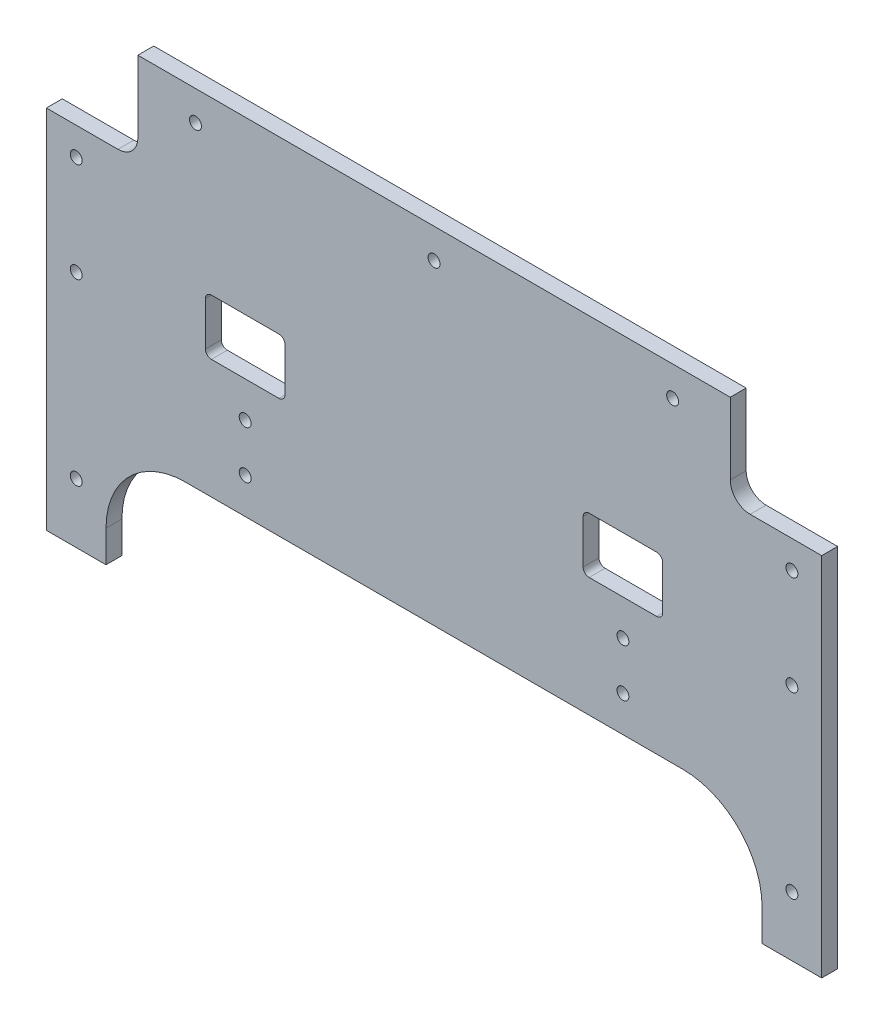
SolidWorks part; units mm, degrees
material "Thornel Mat VMA"
ref_plane "前视基准面" through (0, 0, 0) normal (0, 0, 1) x (1, 0, 0)
ref_plane "上视基准面" through (0, 0, 0) normal (0, 1, 0) x (1, 0, 0)
ref_plane "右视基准面" through (0, 0, 0) normal (1, 0, 0) x (0, 0, -1)
sketch "草图1" plane through (0, 0, 0) normal (0, 0, 1) x (1, 0, 0)
  line L1 (-97.5, 25) -> (97.5, 25)
  line L2 (-97.5, 25) -> (-97.5, -25)
  line L3 (-97.5, -25) -> (97.5, -25)
  line L4 (97.5, 25) -> (97.5, -25)
  line L5 (-97.5, 25) -> (97.5, -25) construction
  line L6 (-97.5, -25) -> (97.5, 25) construction
  point P0 (0, 0)
  dimension "D1" = 195
  dimension "D2" = 50
extrude "凸台-拉伸1" add sketch "草图1" along normal blind 4
sketch "草图5" plane through (0, 0, 4) normal (0, 0, 1) x (1, 0, 0)
  line L0 (0, 0) -> (0, 50) construction
  line L1 (97.5, 25) -> (-97.5, 25) construction
  line L2 (-97.5, 75) -> (97.5, 75)
  line L3 (-97.5, 75) -> (-97.5, 25)
  line L4 (-97.5, 25) -> (97.5, 25)
  line L5 (97.5, 75) -> (97.5, 25)
  line L6 (-97.5, 75) -> (97.5, 25) construction
  line L7 (-97.5, 25) -> (97.5, 75) construction
  line L8 (-97.5, 25) -> (-97.5, -25) construction
  dimension "D1" = 50
extrude "凸台-拉伸2" add sketch "草图5" against normal up to surface (4 mm away) up to face at (0, 0, 0)
sketch "草图2" plane through (0, 0, 4) normal (0, 0, 1) x (1, 0, 0)
  line L0 (0, 75) -> (0, -25) construction
  line L2 (-97.5, -25) -> (97.5, -25) construction
  line L3 (97.5, 75) -> (-97.5, 75) construction
  line L4 (-47.5, 9) -> (47.5, 9) construction
  line L5 (-47.5, 9) -> (-47.5, -3) construction
  line L6 (-47.5, -3) -> (47.5, -3) construction
  line L7 (47.5, 9) -> (47.5, -3) construction
  line L8 (-47.5, 9) -> (47.5, -3) construction
  line L9 (-47.5, -3) -> (47.5, 9) construction
  circle A0 centre (-47.5, -3) radius 1.5
  circle A1 centre (-47.5, 9) radius 1.5
  circle A2 centre (47.5, 9) radius 1.5
  circle A3 centre (47.5, -3) radius 1.5
  point P6 (0, 3)
  dimension "D4" = 3
  dimension "D1" = 12
  dimension "D2" = 95
  dimension "D3" = 28
extrude "切除-拉伸1" cut sketch "草图2" against normal through all
sketch "草图4" plane through (0, 0, 4) normal (0, 0, 1) x (1, 0, 0)
  line L0 (0, 75) -> (0, -25) construction
  line L2 (-97.5, -25) -> (97.5, -25) construction
  line L3 (47.5, -3) -> (47.5, 18) construction
  line L4 (37.5, 32) -> (57.5, 32)
  line L5 (37.5, 32) -> (37.5, 18)
  line L6 (37.5, 18) -> (57.5, 18)
  line L7 (57.5, 32) -> (57.5, 18)
  line L8 (-57.5, 32) -> (-57.5, 18)
  line L9 (-37.5, 18) -> (-57.5, 18)
  line L10 (-37.5, 32) -> (-37.5, 18)
  line L11 (-37.5, 32) -> (-57.5, 32)
  line L12 (97.5, 75) -> (-97.5, 75) construction
  dimension "D1" = 43
  dimension "D2" = 20
  dimension "D3" = 14
extrude "切除-拉伸3" cut sketch "草图4" against normal through all
fillet "圆角1" radius 1.5 8 edges at (57.5, 18, 2) (57.5, 32, 2) (37.5, 32, 2) (37.5, 18, 2) (-57.5, 18, 2) (-37.5, 18, 2) (-37.5, 32, 2) (-57.5, 32, 2)
sketch "草图6" plane through (0, 0, 4) normal (0, 0, 1) x (1, 0, 0)
  line L0 (0, 75) -> (0, -25) construction
  line L1 (-97.5, 75) -> (-74.5, 75)
  line L2 (-97.5, 75) -> (-97.5, 52)
  line L3 (-97.5, 52) -> (-74.5, 52)
  line L4 (-74.5, 75) -> (-74.5, 52)
  line L5 (97.5, 75) -> (-97.5, 75) construction
  line L6 (-97.5, -25) -> (97.5, -25) construction
  line L7 (74.5, 75) -> (74.5, 52)
  line L8 (97.5, 52) -> (74.5, 52)
  line L9 (97.5, 75) -> (97.5, 52)
  line L10 (97.5, 75) -> (74.5, 75)
  dimension "D1" = 23
  dimension "D2" = 23
extrude "切除-拉伸4" cut sketch "草图6" against normal through all
fillet "圆角2" radius 5 2 edges at (74.5, 52, 2) (-74.5, 52, 2)
sketch "草图7" plane through (0, 0, 4) normal (0, 0, 1) x (1, 0, 0)
  line L0 (0, 0) -> (0, -25) construction
  line L1 (-97.5, -25) -> (97.5, -25) construction
  line L2 (82.5, -25) -> (82.5, -40)
  line L3 (-97.5, -25) -> (-82.5, -25)
  line L4 (-97.5, -25) -> (-97.5, -40)
  line L5 (-97.5, -40) -> (-82.5, -40)
  line L6 (-82.5, -25) -> (-82.5, -40)
  line L7 (97.5, -40) -> (82.5, -40)
  line L8 (97.5, -25) -> (97.5, -40)
  line L9 (97.5, -25) -> (82.5, -25)
  dimension "D1" = 15
  dimension "D2" = 15
extrude "凸台-拉伸3" add sketch "草图7" against normal up to surface (4 mm away) up to face at (47.5, 25, 0)
sketch "草图3" plane through (0, 0, 4) normal (0, 0, 1) x (1, 0, 0)
  line L0 (0, 75) -> (0, -25) construction
  line L2 (-82.5, -25) -> (82.5, -25) construction
  line L3 (97.5, -40) -> (97.5, 52) construction
  line L4 (-90, 45) -> (90, 45) construction
  line L5 (-90, 45) -> (-90, -25) construction
  line L6 (-90, -25) -> (90, -25) construction
  line L7 (90, 45) -> (90, -25) construction
  line L8 (-90, 45) -> (90, -25) construction
  line L9 (-90, -25) -> (90, 45) construction
  line L10 (74.5, 75) -> (-74.5, 75) construction
  line L11 (-90, 10) -> (90, 10) construction
  circle A0 centre (-90, 45) radius 1.5
  circle A1 centre (-90, -25) radius 1.5
  circle A2 centre (90, -25) radius 1.5
  circle A3 centre (90, 45) radius 1.5
  circle A4 centre (-90, 20) radius 1.5
  circle A5 centre (90, 20) radius 1.5
  point P6 (0, 10)
  dimension "D4" = 3
  dimension "D5" = 45
  dimension "D1" = 7.5
  dimension "D2" = 30
  dimension "D3" = 70
extrude "切除-拉伸2" cut sketch "草图3" against normal through all
sketch "草图8" plane through (0, 0, 4) normal (0, 0, 1) x (1, 0, 0)
  line L0 (0, 75) -> (0, -25) construction
  line L1 (74.5, 75) -> (-74.5, 75) construction
  line L2 (-82.5, -25) -> (82.5, -25) construction
  circle A0 centre (0, 67.5) radius 1.5
  circle A1 centre (-60, 67.5) radius 1.5
  circle A2 centre (60, 67.5) radius 1.5
  dimension "D1" = 7.5
  dimension "D2" = 3
  dimension "D3" = 60
extrude "切除-拉伸5" cut sketch "草图8" against normal through all
sketch "草图9" plane through (0, 0, 4) normal (0, 0, 1) x (1, 0, 0)
  line L0 (82.5, -25) -> (82.5, -40) construction
  line L1 (-82.5, -25) -> (82.5, -25)
  line L2 (-82.5, -25) -> (-82.5, -12)
  line L3 (-82.5, -12) -> (82.5, -12)
  line L4 (82.5, -25) -> (82.5, -12)
  dimension "D1" = 13
extrude "切除-拉伸6" cut sketch "草图9" against normal through all
fillet "圆角3" radius 20 2 edges at (82.5, -12, 2) (-82.5, -12, 2)
